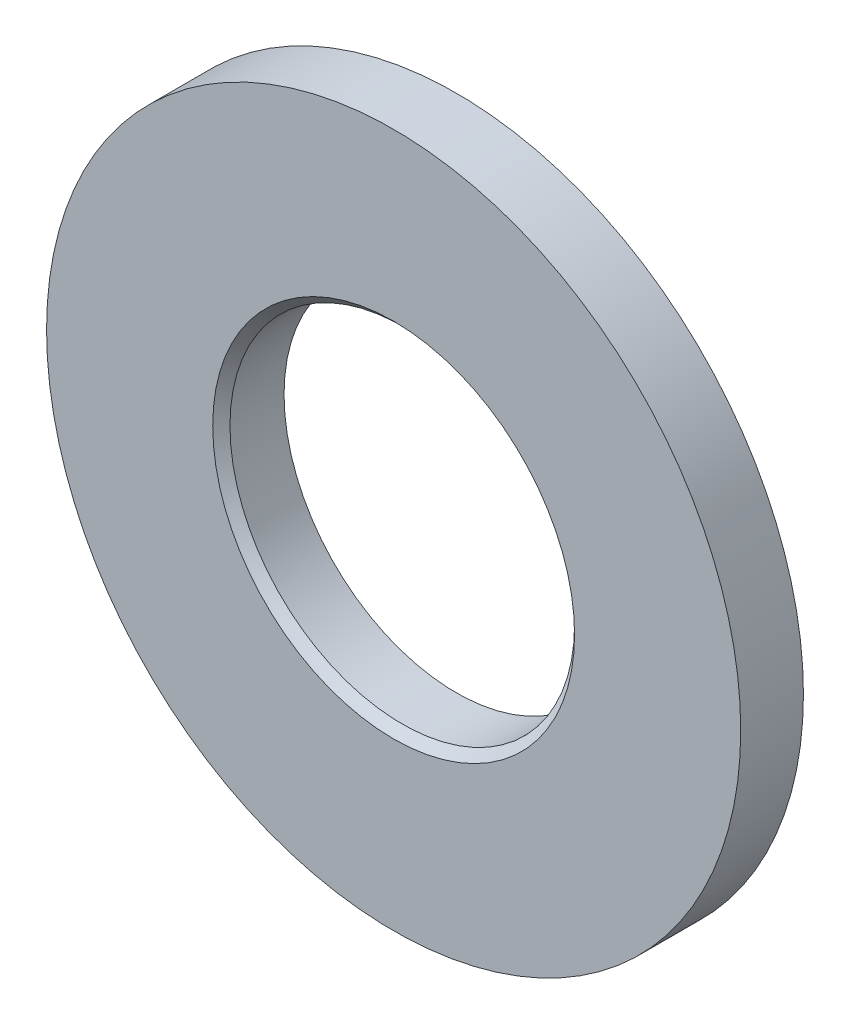
SolidWorks part; units mm, degrees
material "Alloy Steel"
ref_plane "Front Plane" through (0, 0, 0) normal (0, 0, 1) x (1, 0, 0)
ref_plane "Top Plane" through (0, 0, 0) normal (0, 1, 0) x (1, 0, 0)
ref_plane "Right Plane" through (0, 0, 0) normal (1, 0, 0) x (0, 0, -1)
sketch "Sketch1" plane through (0, 0, 0) normal (0, 0, 1) x (1, 0, 0)
  line L0 (-8.9281, 0) -> (8.9281, 0) construction
  line L1 (0, -8.9281) -> (0, 8.9281) construction
  circle A0 centre (0, 0) radius 8.9281
  circle A1 centre (0, 0) radius 4.4323
  point P4 (0, 0)
  point P9 (0, 0)
  dimension "ID" = 8.8646
  dimension "OD" = 17.8562
sketch "Sketch2" plane through (0, 0, 0) normal (1, 0, 0) x (0, 0, -1)
  line L0 (0.8065, 8.9281) -> (-0.8065, 8.9281) construction
  line L1 (0, 8.9281) -> (0, -8.9281) construction
  point P4 (0, 8.9281)
  dimension "Thickness" = 1.6129
sketch "Sketch3" plane through (0, 0, 0) normal (0, 0, 1) x (1, 0, 0)
  line L0 (0, -8.9281) -> (0, 8.9281) construction
  circle A0 centre (0, 0) radius 8.9281
  circle A1 centre (0, 0) radius 4.4323
  circle A2 centre (0, 0) radius 4.4323 construction
extrude "Boss-Extrude1" add sketch "Sketch3" along normal mid plane 1.6129
chamfer "Chamfer1" distance 0.2216 angle 45 1 edges at (4.4323, 0, 0.8065)
equation "\"D1@Boss-Extrude1\" = \"Thickness@Sketch2\""
equation "\"D1@Chamfer1\"=\"ID@Sketch1\"*.025"
